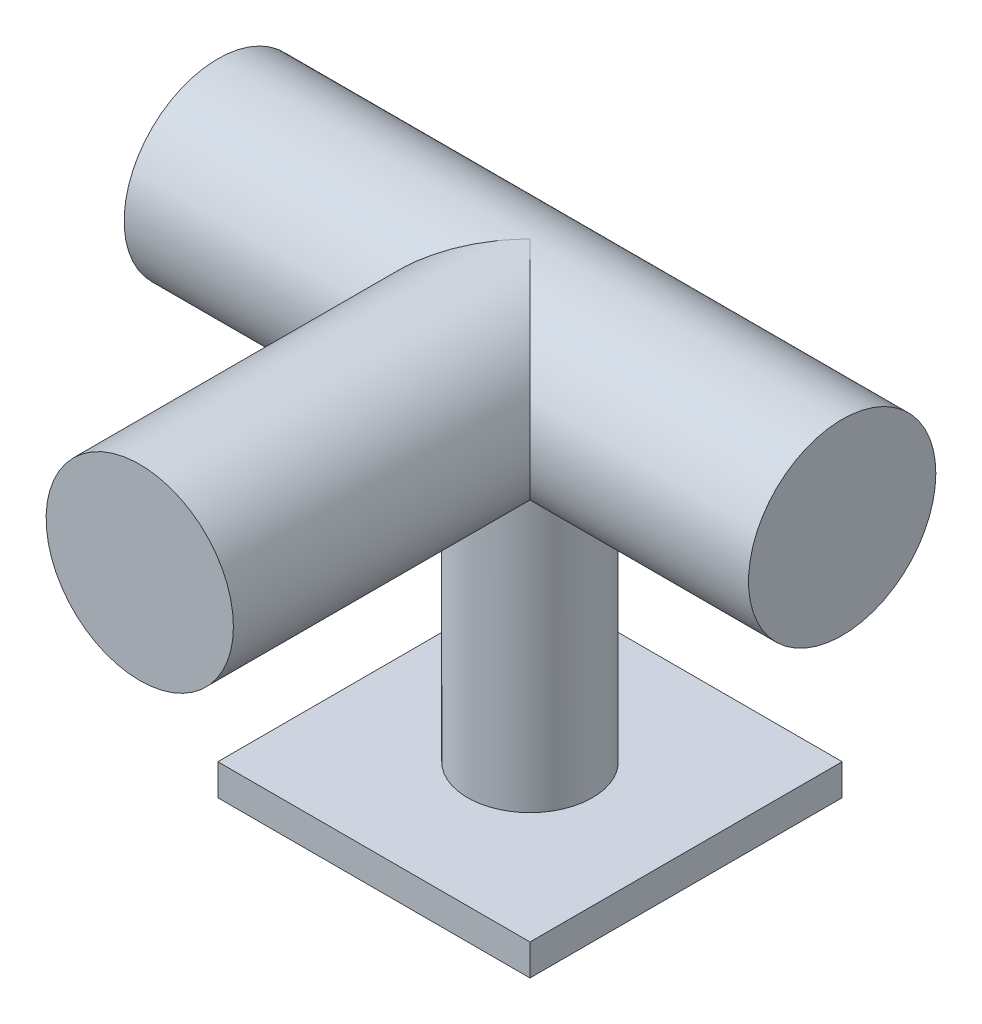
SolidWorks part; units mm, degrees
ref_plane "Front Plane" through (0, 0, 0) normal (0, 0, 1) x (1, 0, 0)
ref_plane "Top Plane" through (0, 0, 0) normal (0, 1, 0) x (1, 0, 0)
ref_plane "Right Plane" through (0, 0, 0) normal (1, 0, 0) x (0, 0, -1)
other "Configuration Table"
sketch "Sketch1" plane through (0, 0, 0) normal (1, 0, 0) x (0, 0, -1)
  circle A0 centre (0, 25) radius 6
  dimension "D1" = 12
extrude "Run" add sketch "Sketch1" along normal blind 40 from offset 20
sketch "Sketch2" plane through (0, 0, 0) normal (0, 0, 1) x (1, 0, 0)
  circle A0 centre (0, 25) radius 6
  dimension "D1" = 12
extrude "Branch" add sketch "Sketch2" along normal blind 25
sketch "Sketch3" plane through (0, 0, 0) normal (0, 1, 0) x (1, 0, 0)
  circle A0 centre (0, 0) radius 4
extrude "Support_Post" add sketch "Sketch3" along normal blind 20
sketch "Sketch4" plane through (0, 0, 0) normal (0, 1, 0) x (1, 0, 0)
  line L1 (-10, -10) -> (10, -10)
  line L2 (-10, -10) -> (-10, 10)
  line L3 (-10, 10) -> (10, 10)
  line L4 (10, -10) -> (10, 10)
  line L5 (-10, -10) -> (10, 10) construction
  line L6 (-10, 10) -> (10, -10) construction
extrude "Support_Foot" add sketch "Sketch4" along normal blind 2
equation "\"tee_L\"= 40.0   'ASSUMPTION: Tee run overall length (PDF fallback)"
equation "\"tee_B\"= 25.0   'ASSUMPTION: Tee branch length from run axis (PDF fallback)"
equation "\"tee_OD\"= 12.0   'ASSUMPTION: Tee OD (PDF fallback)"
equation "\"axis_h\"= 25.0   'ASSUMPTION: Height of the water-line axis above the plate (designer choice)"
equation "\"D1@Sketch1\" = \"tee_OD\""
equation "\"D1@Run\" = \"tee_L\""
equation "\"D1@Sketch2\" = \"tee_OD\""
equation "\"D1@Branch\" = \"tee_B\""
